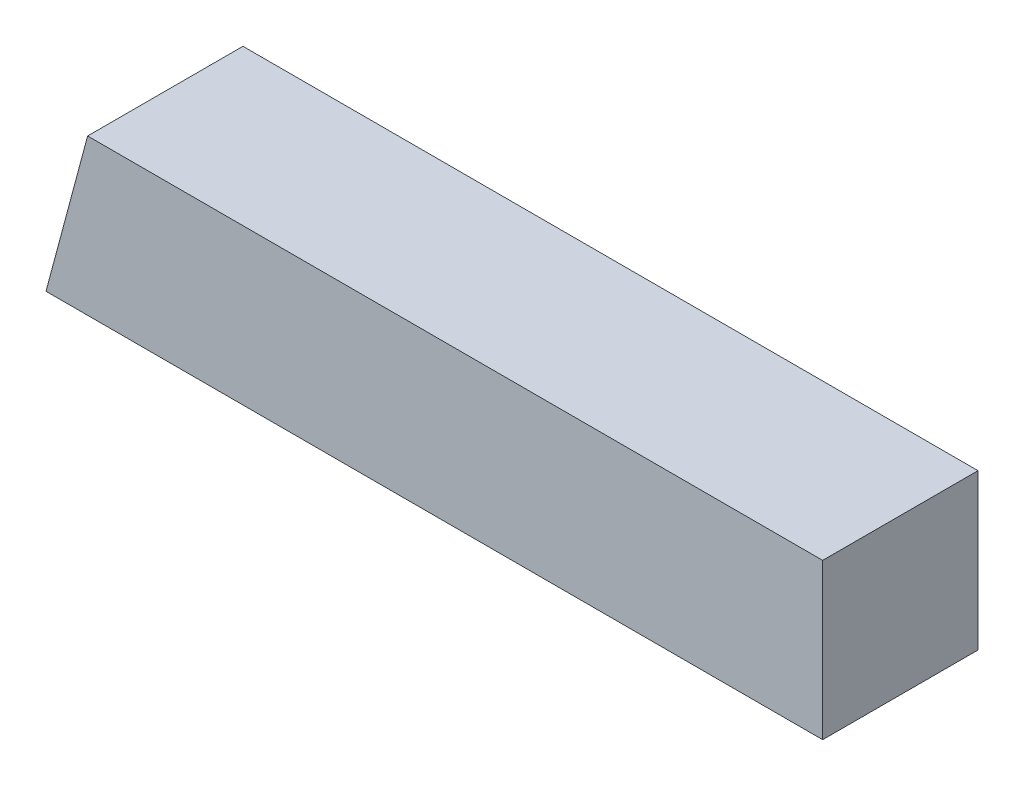
SolidWorks part; units mm, degrees
ref_plane "Plan de face" through (0, 0, 0) normal (0, 0, 1) x (1, 0, 0)
ref_plane "Plan de dessus" through (0, 0, 0) normal (0, 1, 0) x (1, 0, 0)
ref_plane "Plan de droite" through (0, 0, 0) normal (1, 0, 0) x (0, 0, -1)
sketch "Esquisse1" plane through (0, 0, 0) normal (0, 0, 1) x (1, 0, 0)
  line L0 (-43.3444, -15.2298) -> (-35.3059, 14.7702)
  line L1 (-43.3444, -15.2298) -> (106.6556, -15.2298)
  line L3 (-35.3059, 14.7702) -> (106.6556, 14.7702)
  line L4 (106.6556, -15.2298) -> (106.6556, 14.7702)
  dimension "D1" = 150
  dimension "D2" = 30
  dimension "D3" = 105
extrude "Boss.-Extru.1" add sketch "Esquisse1" along normal blind 30
